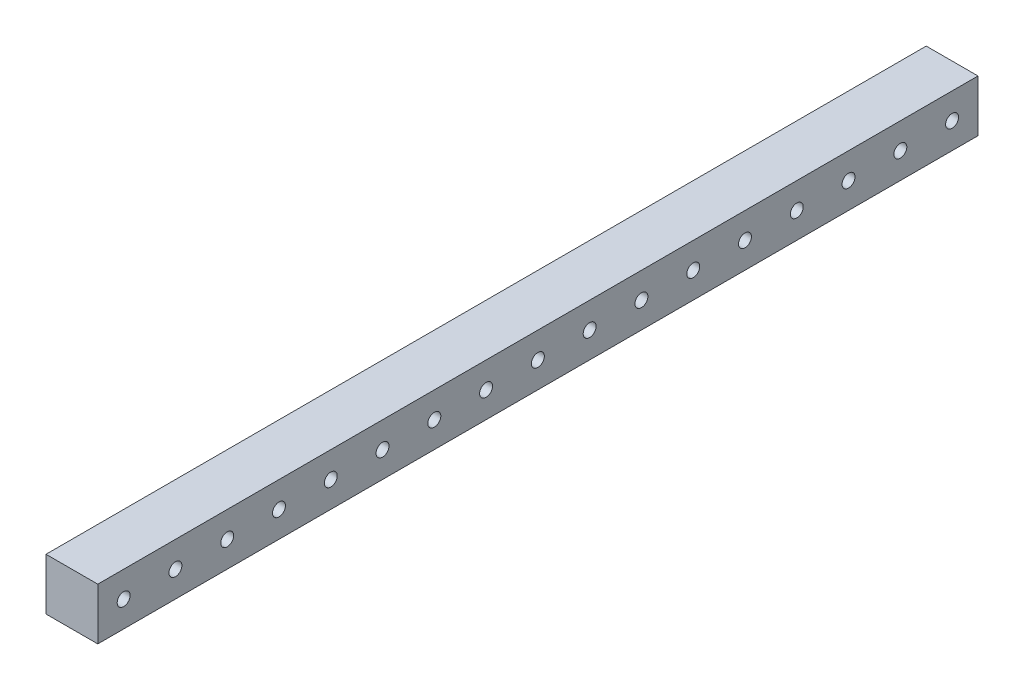
SolidWorks part; units mm, degrees
material "Pine"
ref_plane "Front Plane" through (0, 0, 0) normal (0, 0, 1) x (1, 0, 0)
ref_plane "Top Plane" through (0, 0, 0) normal (0, 1, 0) x (1, 0, 0)
ref_plane "Right Plane" through (0, 0, 0) normal (1, 0, 0) x (0, 0, -1)
sketch "Sketch1" plane through (0, 0, 0) normal (0, 0, 1) x (1, 0, 0)
  line L0 (-10, -10) -> (10, 10) construction
  line L1 (-10, 10) -> (10, 10)
  line L2 (-10, 10) -> (-10, -10)
  line L3 (-10, -10) -> (10, -10)
  line L4 (10, 10) -> (10, -10)
  point P4 (0, 0)
  dimension "D1" = 20
  dimension "D2" = 45
extrude "Boss-Extrude1" add sketch "Sketch1" along normal blind 340
hole_wizard "Ø5.0mm Dowel Hole1" positions "Sketch2" profile "Sketch3" hole size "Ø5.0" standard "ANSI Metric" end condition through all
sketch "Sketch2" plane through (10, 0, 0) normal (1, 0, 0) x (0, 0, -1)
  line L0 (0, -10) -> (0, 10) construction
  point P0 (-10, 0)
  point P7 (0, 0)
  dimension "D1" = 10
sketch "Sketch3" plane through (10, 0, 10) normal (0, 1, 0) x (0, 0, -1)
  line L0 (0, 0) -> (0, 20)
  line L1 (0, 20) -> (2.5, 20)
  line L2 (2.5, 20) -> (2.5, 0)
  line L5 (2.5, 0) -> (0, 0)
  line L11 (0, -6.35) -> (0, 107.95) construction
  dimension "Thru Hole Dia." = 5
  dimension "Thru Hole Depth" = 20
pattern_linear "LPattern2" count 17 spacing 20 along (0, 0, 1) of "Ø5.0mm Dowel Hole1"
